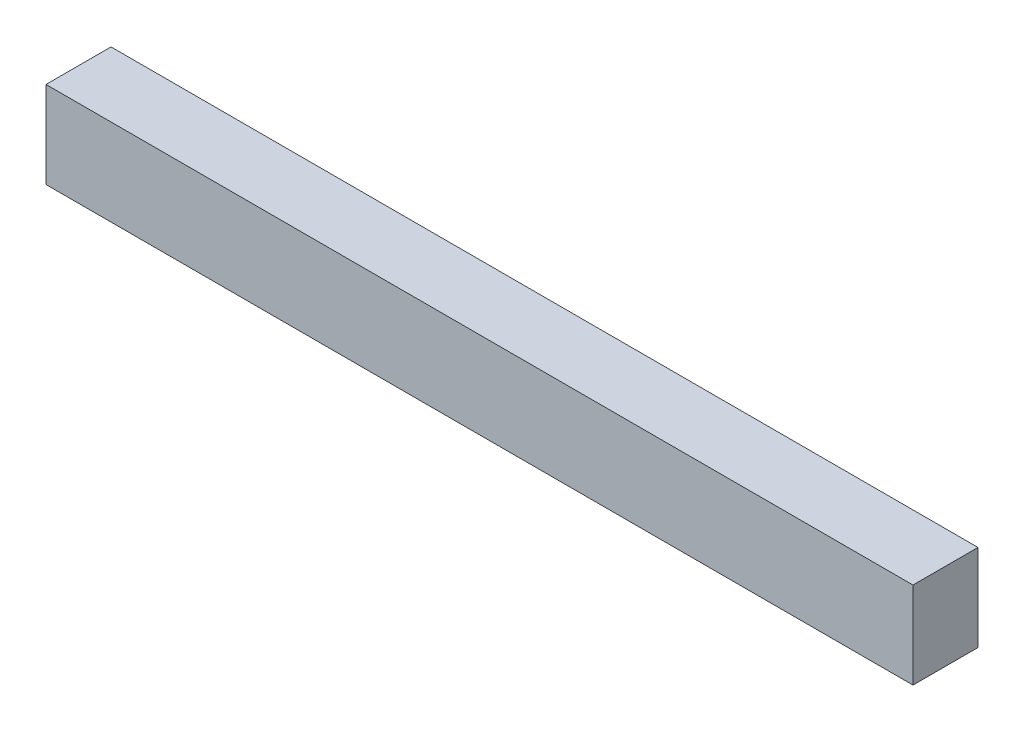
SolidWorks part; units mm, degrees
ref_plane "Plan de face" through (0, 0, 0) normal (0, 0, 1) x (1, 0, 0)
ref_plane "Plan de dessus" through (0, 0, 0) normal (0, 1, 0) x (1, 0, 0)
ref_plane "Plan de droite" through (0, 0, 0) normal (1, 0, 0) x (0, 0, -1)
sketch "Esquisse1" plane through (0, 0, 0) normal (0, 0, 1) x (1, 0, 0)
  line L0 (0, -469.4099) -> (0, -659.4099) construction
  line L1 (400, -469.4099) -> (0, -469.4099)
  line L2 (400, -469.4099) -> (400, -509.4099)
  line L3 (400, -509.4099) -> (0, -509.4099)
  line L4 (0, -469.4099) -> (0, -509.4099)
  dimension "D1" = 40
extrude "Boss.-Extru.1" add sketch "Esquisse1" along normal blind 30
